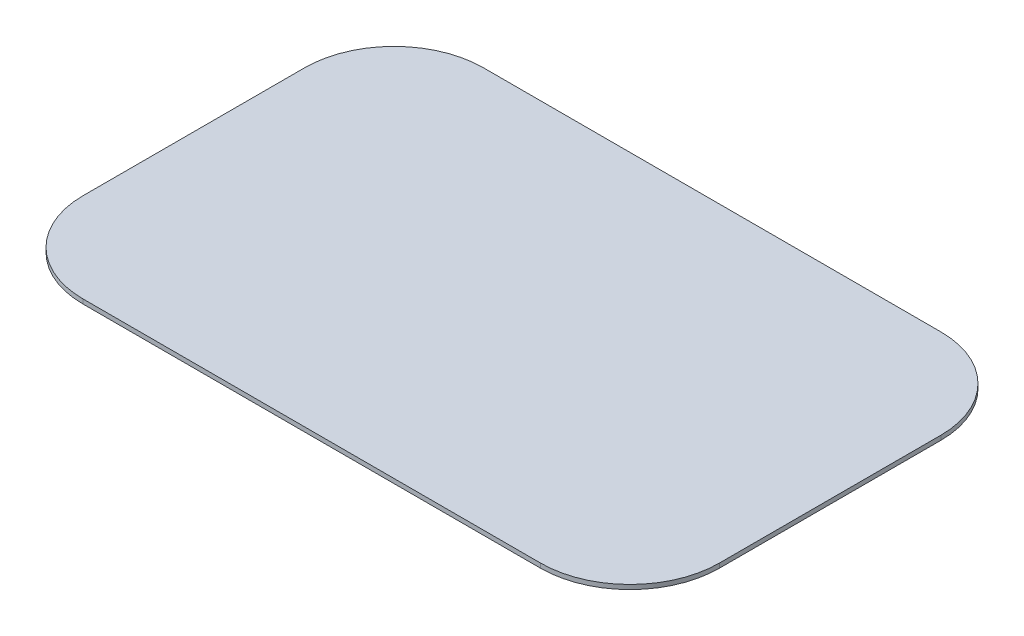
SolidWorks part; units mm, degrees
material "Beton"
ref_plane "Płaszczyzna przednia" through (0, 0, 0) normal (0, 0, 1) x (1, 0, 0)
ref_plane "Płaszczyzna górna" through (0, 0, 0) normal (0, 1, 0) x (1, 0, 0)
ref_plane "Płaszczyzna prawa" through (0, 0, 0) normal (1, 0, 0) x (0, 0, -1)
sketch "Szkic1" plane through (0, 0, 0) normal (0, 1, 0) x (1, 0, 0)
  line L9 (1000, 0) -> (6120, 0)
  line L10 (0, -1000) -> (0, -3480)
  line L11 (1000, -4480) -> (6120, -4480)
  line L12 (7120, -1000) -> (7120, -3480)
  arc A4 (1000, 0) -> (0, -1000) centre (1000, -1000) ccw
  arc A5 (0, -3480) -> (1000, -4480) centre (1000, -3480) ccw
  arc A6 (6120, -4480) -> (7120, -3480) centre (6120, -3480) ccw
  arc A7 (6120, 0) -> (7120, -1000) centre (6120, -1000) cw
  point P6 (0, 0)
  point P9 (0, -4480)
  point P14 (7120, 0)
  dimension "D4" = 1000
  dimension "D3" = 1000
  dimension "D5" = 1000
  dimension "D6" = 1000
  dimension "D1" = 4480
  dimension "D2" = 7120
extrude "Dodanie-wyciągnięcie1" add sketch "Szkic1" against normal blind 50 contours L11 A6 L12 A7 L9 A4 L10 A5
sketch "Szkic2" plane through (0, 0, 0) normal (0, 1, 0) x (1, 0, 0)
  line L0 (1250, -1350) -> (1250, -3853.6925) construction
  line L1 (1250, -1350) -> (5294.5441, -1350) construction
  line L6 (1000, -1000) -> (1000, -3480)
  line L7 (1000, -3480) -> (6120, -3480)
  line L8 (1000, -1000) -> (6120, -1000)
  line L9 (6120, -1000) -> (6120, -3480)
  point P3 (1250, -2738.5145)
  point P6 (1250, -3853.6925)
  point P7 (5294.5441, -1250)
  dimension "D1" = 250
  dimension "D2" = 350
